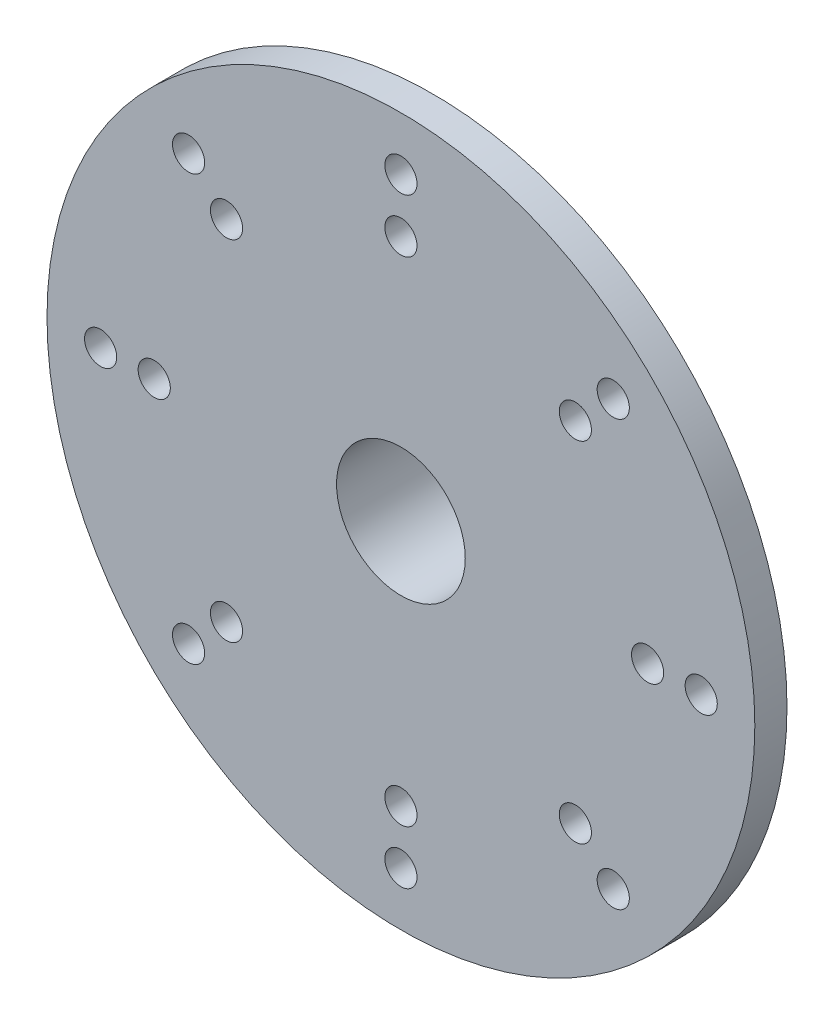
SolidWorks part; units mm, degrees
ref_plane "Front" through (0, 0, 0) normal (0, 0, 1) x (1, 0, 0)
ref_plane "Top" through (0, 0, 0) normal (0, 1, 0) x (1, 0, 0)
ref_plane "Right" through (0, 0, 0) normal (1, 0, 0) x (0, 0, -1)
sketch "草图1" plane through (0, 0, 0) normal (0, 0, 1) x (1, 0, 0)
  circle A0 centre (0, 0) radius 4
  circle A1 centre (0, 0) radius 3
  dimension "D1" = 6
  dimension "D2" = 8
extrude "凸台-拉伸1" add sketch "草图1" along normal blind 6
sketch "草图2" plane through (0, 0, 6) normal (0, 0, 1) x (1, 0, 0)
  circle A0 centre (0, 0) radius 4
  circle A1 centre (0, 0) radius 16.5
extrude "凸台-拉伸2" add sketch "草图2" against normal blind 1.5
sketch "草图4" plane through (0, 0, 6) normal (0, 0, 1) x (1, 0, 0)
  line L0 (0, 17.8293) -> (0, -24.521) construction
  circle A0 centre (0, 14) radius 0.75
  circle A1 centre (0, 11.5) radius 0.75
  dimension "D1" = 1.5
  dimension "D3" = 1.5
  dimension "D2" = 14
  dimension "D4" = 11.5
extrude "切除-拉伸1" cut sketch "草图4" against normal blind 1.5
pattern_circular "阵列(圆周)1" count 8 over 360 about axis through (0, 0, 4.5) along (0, 0, 1) of "切除-拉伸1"
